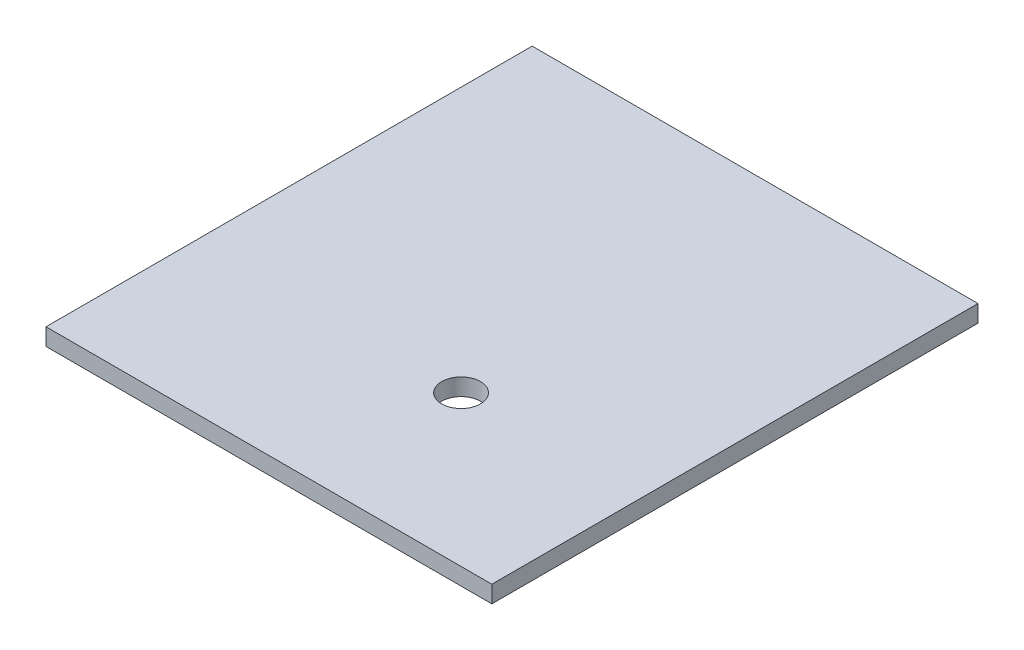
SolidWorks part; units mm, degrees
ref_plane "Front Plane" through (0, 0, 0) normal (0, 0, 1) x (1, 0, 0)
ref_plane "Top Plane" through (0, 0, 0) normal (0, 1, 0) x (1, 0, 0)
ref_plane "Right Plane" through (0, 0, 0) normal (1, 0, 0) x (0, 0, -1)
sketch "Sketch1" plane through (0, 0, 0) normal (0, 1, 0) x (1, 0, 0)
  line L1 (-73.025, -79.629) -> (73.025, -79.629)
  line L2 (-73.025, -79.629) -> (-73.025, 79.629)
  line L3 (-73.025, 79.629) -> (73.025, 79.629)
  line L4 (73.025, -79.629) -> (73.025, 79.629)
  line L5 (-73.025, -79.629) -> (73.025, 79.629) construction
  line L6 (-73.025, 79.629) -> (73.025, -79.629) construction
  point P0 (0, 0)
  dimension "D1" = 146.05
  dimension "D2" = 159.258
extrude "Boss-Extrude1" add sketch "Sketch1" along normal blind 5.588
sketch "Sketch4" plane through (0, 5.588, 0) normal (0, 1, 0) x (1, 0, 0)
  line L0 (-73.025, -79.629) -> (73.025, -79.629) construction
  line L1 (73.025, -79.629) -> (73.025, 79.629) construction
  circle A4 centre (13.6706, -30.353) radius 6.35
  dimension "D1" = 12.7
  dimension "D2" = 49.276
  dimension "D3" = 59.3544
extrude "Cut-Extrude1" cut sketch "Sketch4" against normal up to next
